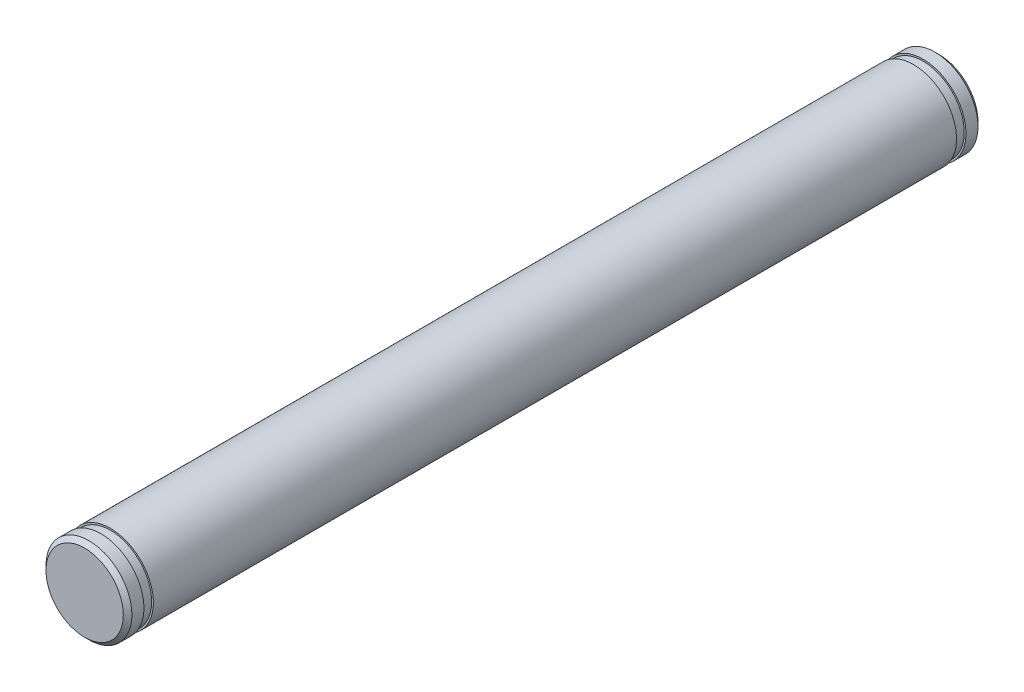
SolidWorks part; units mm, degrees
ref_plane "前视基准面" through (0, 0, 0) normal (0, 0, 1) x (1, 0, 0)
ref_plane "上视基准面" through (0, 0, 0) normal (0, 1, 0) x (1, 0, 0)
ref_plane "右视基准面" through (0, 0, 0) normal (1, 0, 0) x (0, 0, -1)
other "Configuration Table"
sketch "草图1" plane through (0, 0, 0) normal (0, 0, 1) x (1, 0, 0)
  circle A0 centre (0, 0) radius 5
  dimension "D1" = 10
extrude "凸台-拉伸1" add sketch "草图1" along normal blind 99.5
chamfer "倒角1" distance 0.5 angle 45 2 edges at (5, 0, 99.5) (5, 0, 0)
ref_plane "基准面1" through (0, 0, 49.75) normal (0, 0, 1) x (1, 0, 0)
sketch "草图2" plane through (0, 0, 0) normal (0, 0, -1) x (-1, 0, 0)
  circle A0 centre (0, 0) radius 5 construction
  circle A1 centre (0, 0) radius 5
  circle A2 centre (0, 0) radius 4.8
  dimension "D1" = 9.6
extrude "切除-拉伸1" cut sketch "草图2" along normal blind 1.1 from offset 3 offset against normal yes
mirror "镜向1" about plane through (0, 0, 49.75) normal (0, 0, 1) of "切除-拉伸1"
